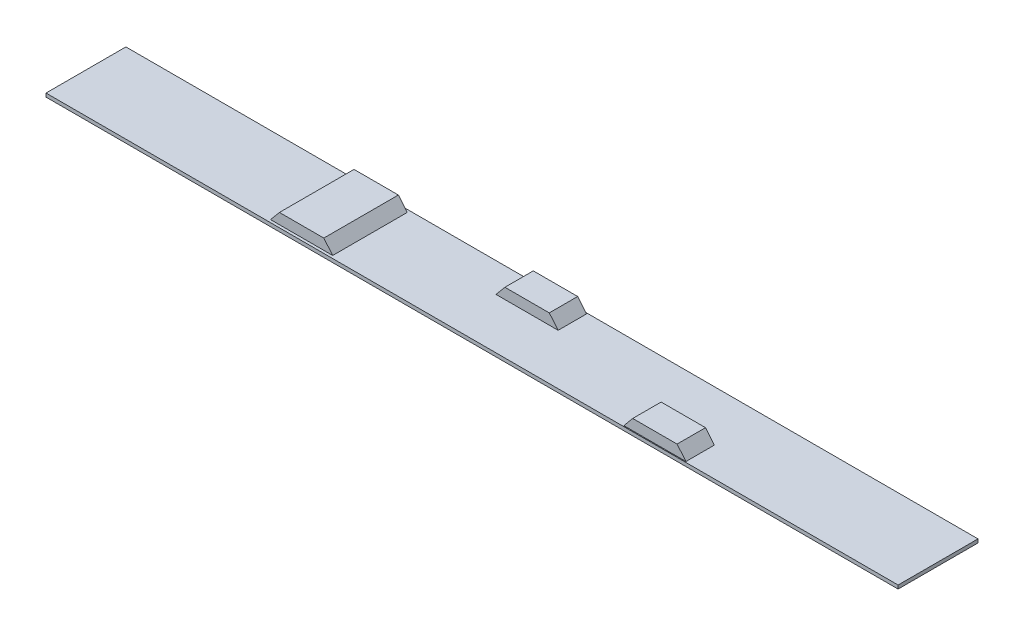
SolidWorks part; units mm, degrees
ref_plane "Front Plane" through (0, 0, 0) normal (0, 0, 1) x (1, 0, 0)
ref_plane "Top Plane" through (0, 0, 0) normal (0, 1, 0) x (1, 0, 0)
ref_plane "Right Plane" through (0, 0, 0) normal (1, 0, 0) x (0, 0, -1)
sketch "Sketch2" plane through (0, 0, 0) normal (0, 1, 0) x (1, 0, 0)
  line L1 (-1200, -112.5) -> (1200, -112.5)
  line L2 (-1200, -112.5) -> (-1200, 112.5)
  line L3 (-1200, 112.5) -> (1200, 112.5)
  line L4 (1200, -112.5) -> (1200, 112.5)
  line L5 (-1200, -112.5) -> (1200, 112.5) construction
  line L6 (-1200, 112.5) -> (1200, -112.5) construction
  point P0 (0, 0)
  dimension "D1" = 2400
  dimension "D2" = 225
extrude "Boss-Extrude1" add sketch "Sketch2" along normal blind 10
sketch "Sketch3" plane through (0, 0, 0) normal (0, 0, 1) x (1, 0, 0)
  line L0 (425, 10) -> (450, 40)
  line L2 (450, 40) -> (575, 40)
  line L3 (575, 40) -> (600, 10)
  line L4 (425, 10) -> (600, 10)
  line L6 (1200, 10) -> (1200, 0) construction
  dimension "D1" = 175
  dimension "D2" = 30
  dimension "D3" = 600
  dimension "D4" = 125
extrude "Boss-Extrude2" add sketch "Sketch3" along normal blind 80 from offset 30
sketch "Sketch4" plane through (0, 0, 0) normal (0, 0, 1) x (1, 0, 0)
  line L0 (-50, 40) -> (-75, 10)
  line L1 (75, 40) -> (-50, 40)
  line L2 (100, 10) -> (75, 40)
  line L3 (-75, 10) -> (100, 10)
  line L4 (450, 40) -> (425, 10)
  line L5 (575, 40) -> (450, 40)
  line L6 (600, 10) -> (575, 40)
  line L7 (425, 10) -> (600, 10)
  line L8 (450, 40) -> (425, 10) construction
  line L9 (575, 40) -> (450, 40) construction
  line L10 (600, 10) -> (575, 40) construction
  line L11 (425, 10) -> (600, 10) construction
  dimension "D1" = 0
  dimension "D2" = 2
extrude "Boss-Extrude3" add sketch "Sketch4" along normal blind 80 from offset 110 offset against normal yes
sketch "Sketch5" plane through (0, 0, 0) normal (0, 0, 1) x (1, 0, 0)
  line L0 (-550, 40) -> (-575, 10)
  line L1 (-575, 10) -> (-400, 10)
  line L2 (-400, 10) -> (-425, 40)
  line L3 (-425, 40) -> (-550, 40)
  line L4 (-50, 40) -> (-75, 10)
  line L5 (-75, 10) -> (100, 10)
  line L6 (100, 10) -> (75, 40)
  line L7 (75, 40) -> (-50, 40)
  line L8 (-50, 40) -> (-75, 10) construction
  line L9 (-75, 10) -> (100, 10) construction
  line L10 (100, 10) -> (75, 40) construction
  line L11 (75, 40) -> (-50, 40) construction
  dimension "D1" = 0
  dimension "D2" = 2
extrude "Boss-Extrude4" add sketch "Sketch5" along normal blind 105 and the other way blind 105
